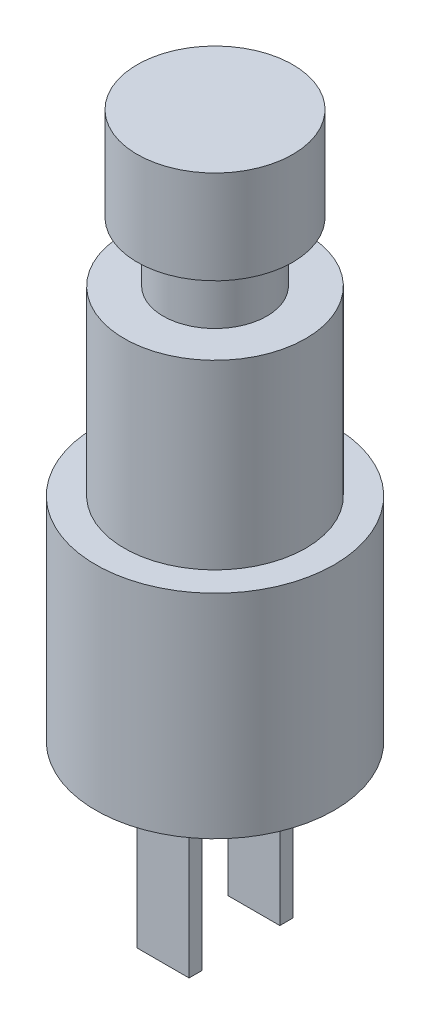
SolidWorks part; units mm, degrees
ref_plane "Front" through (0, 0, 0) normal (0, 0, 1) x (1, 0, 0)
ref_plane "Top" through (0, 0, 0) normal (0, 1, 0) x (1, 0, 0)
ref_plane "Right" through (0, 0, 0) normal (1, 0, 0) x (0, 0, -1)
sketch "Эскиз1" plane through (0, 0, 0) normal (0, 0, 1) x (1, 0, 0)
  line L0 (0, 0) -> (0, 21.1)
  line L1 (0, 21.1) -> (3, 21.1)
  line L2 (3, 21.1) -> (3, 17.5)
  line L3 (3, 17.5) -> (2, 17.5)
  line L4 (2, 17.5) -> (2, 15.2)
  line L5 (2, 15.2) -> (3.5, 15.2)
  line L6 (3.5, 15.2) -> (3.5, 8.2)
  line L7 (3.5, 8.2) -> (4.6, 8.2)
  line L12 (4.6, 8.2) -> (4.6, 0)
  line L13 (4.6, 0) -> (0, 0)
  dimension "D1" = 3
  dimension "D2" = 3.6
  dimension "D3" = 2.3
  dimension "D4" = 7
  dimension "D5" = 8.2
  dimension "D6" = 1
  dimension "D7" = 3.5
  dimension "D8" = 4.6
revolve "Кнопка" add sketch "Эскиз1" angle 360 about L0
sketch "Эскиз2" plane through (0, 0, 0) normal (0, -1, 0) x (1, 0, 0)
  line L0 (-1, 1.5) -> (-1, 2)
  line L1 (-1, 2) -> (1, 2)
  line L2 (1, 2) -> (1, 1.5)
  line L3 (1, 1.5) -> (-1, 1.5)
  line L4 (0, 0) -> (0, 4.6) construction
  line L5 (0, 0) -> (4.6, 0) construction
  line L6 (1, -1.5) -> (-1, -1.5)
  line L7 (1, -2) -> (1, -1.5)
  line L8 (-1, -2) -> (1, -2)
  line L9 (-1, -1.5) -> (-1, -2)
  circle A0 centre (0, 0) radius 4.6 construction
  point P10 (0, 1.5)
  point P16 (1, 1.75)
  point P17 (1, -1.75)
  dimension "D1" = 2
  dimension "D2" = 3.5
  dimension "D3" = 0.5
extrude "Контакты" add sketch "Эскиз2" along normal blind 6.4
